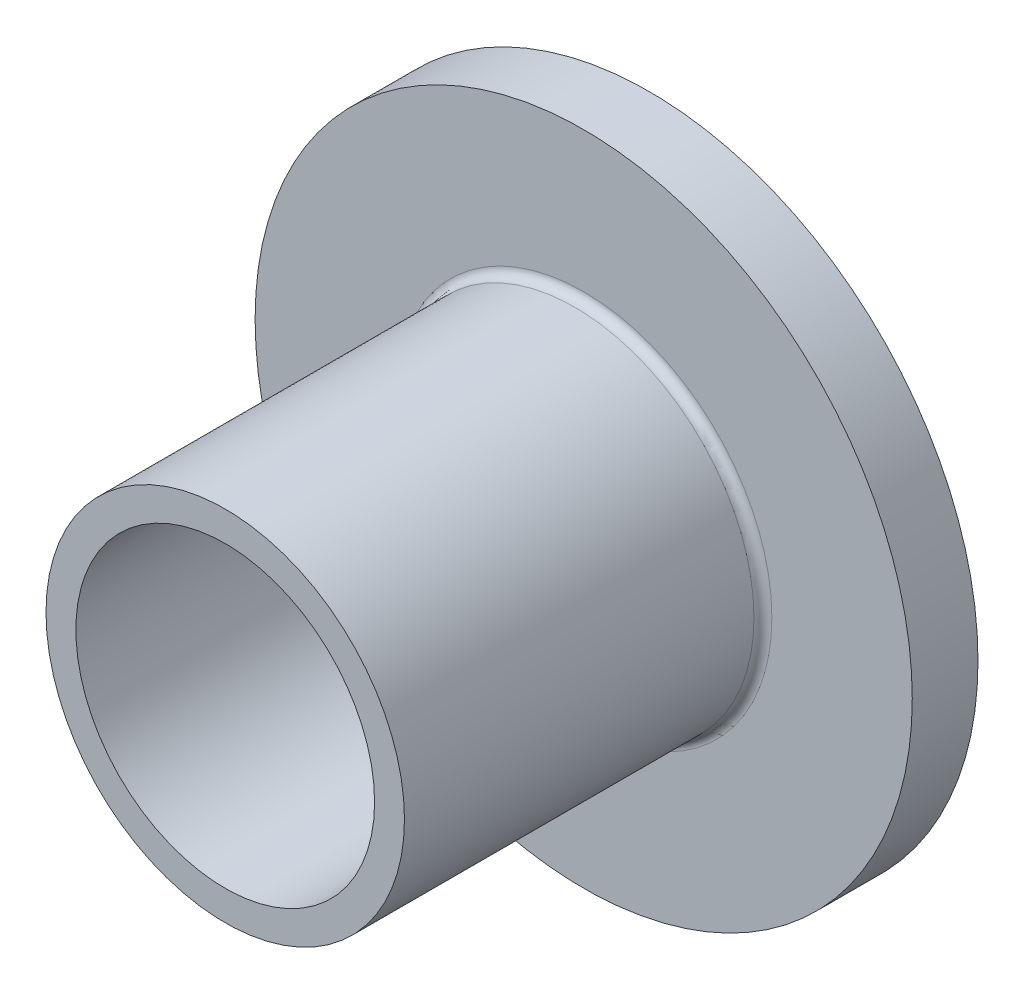
SolidWorks part; units mm, degrees
ref_plane "Front Plane" through (0, 0, 0) normal (0, 0, 1) x (1, 0, 0)
ref_plane "Top Plane" through (0, 0, 0) normal (0, 1, 0) x (1, 0, 0)
ref_plane "Right Plane" through (0, 0, 0) normal (1, 0, 0) x (0, 0, -1)
sketch "Sketch1" plane through (0, 0, 0) normal (0, 0, 1) x (1, 0, 0)
  circle A0 centre (0, 0) radius 110
  dimension "D1" = 220
extrude "Boss-Extrude1" add sketch "Sketch1" along normal blind 22
sketch "Sketch2" plane through (0, 0, 22) normal (0, 0, 1) x (1, 0, 0)
  circle A0 centre (0, 0) radius 60
  dimension "D1" = 120
extrude "Boss-Extrude2" add sketch "Sketch2" along normal blind 120 and the other way blind 22 contours A0
sketch "Sketch3" plane through (0, 0, 0) normal (0, 0, 1) x (1, 0, 0)
  circle A0 centre (0, 0) radius 50
  dimension "D1" = 100
extrude "Cut-Extrude3" cut sketch "Sketch3" against normal blind 120 and the other way through all contours A0
fillet "Fillet1" radius 3 1 edges at (60, 0, 22)
